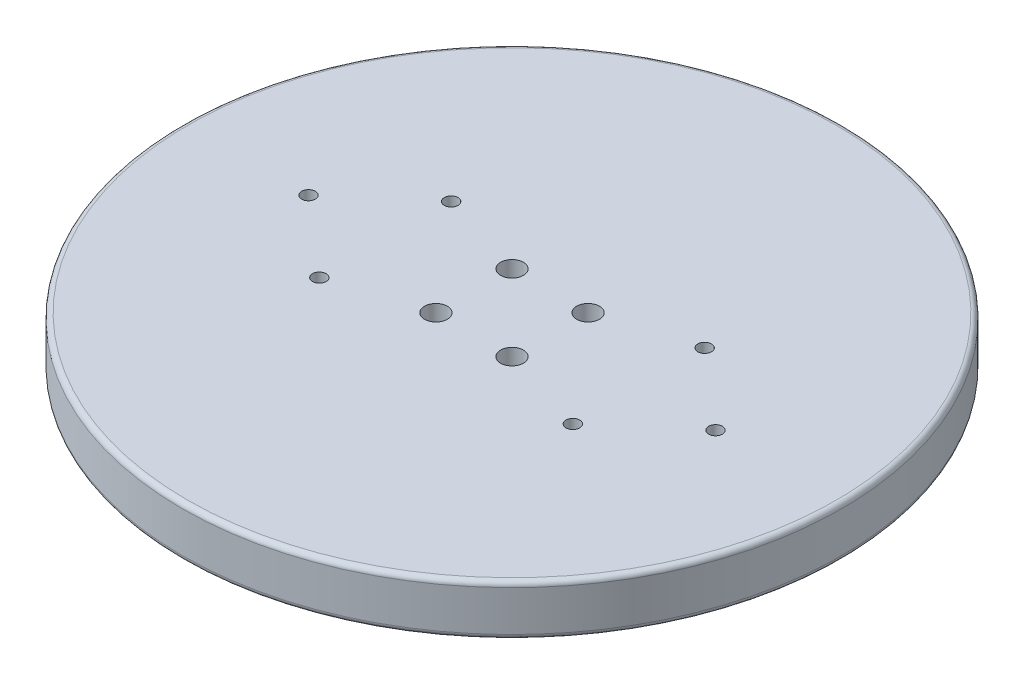
SolidWorks part; units mm, degrees
material "Delrin 2700 NC010, Low Viscosity Acetal Copolymer (SS)"
ref_plane "Front Plane" through (0, 0, 0) normal (0, 0, 1) x (1, 0, 0)
ref_plane "Top Plane" through (0, 0, 0) normal (0, 1, 0) x (1, 0, 0)
ref_plane "Right Plane" through (0, 0, 0) normal (1, 0, 0) x (0, 0, -1)
sketch "Sketch1" plane through (0, 0, 0) normal (0, 1, 0) x (1, 0, 0)
  circle A0 centre (0, 0) radius 65
  dimension "D1" = 130
extrude "Boss-Extrude1" add sketch "Sketch1" along normal blind 10
fillet "Fillet1" radius 1 2 edges at (0, 0, 65) (0, 10, 65)
hole_wizard "#6-32 Tapped Hole1" positions "Sketch2" profile "Sketch3" tap size "#6-32" standard "ANSI Inch" end condition through all
sketch "Sketch2" plane through (0, 0, 0) normal (0, 1, 0) x (1, 0, 0)
  point P0 (-40.14, 0)
  point P2 (40.14, 0)
  point P4 (-25, 13)
  point P6 (-25, -13)
  point P8 (25, -13)
  point P10 (25, 13)
  dimension "D1" = 40.14
  dimension "D2" = 40.14
  dimension "D3" = 25
  dimension "D4" = 25
  dimension "D5" = 13
  dimension "D6" = 13
sketch "Sketch3" plane through (-40.14, 0, 0) normal (1, 0, 0) x (0, 0, -1)
  line L0 (0, 0) -> (0, 10)
  line L1 (0, 10) -> (1.3525, 10)
  line L2 (1.3525, 10) -> (1.3525, 0)
  line L5 (1.3525, 0) -> (0, 0)
  line L11 (0, -6.35) -> (0, 107.95) construction
  dimension "Thru Tap Drill Dia." = 2.7051
  dimension "Thru Tap Drill Depth" = 10
cosmetic thread "Hole Thread1" parameters "D2"=3.5052
cosmetic thread "Hole Thread2" parameters "D2"=3.5052
cosmetic thread "Hole Thread3" parameters "D2"=3.5052
cosmetic thread "Hole Thread4" parameters "D2"=3.5052
cosmetic thread "Hole Thread5" parameters "D2"=3.5052
cosmetic thread "Hole Thread6" parameters "D2"=3.5052
hole_wizard "#4-40 Tapped Hole1" [suppressed] positions "Sketch5" profile "Sketch6" tap size "#4-40" standard "ANSI Inch"
sketch "Sketch5" plane through (0, 0, 0) normal (0, -1, 0) x (-1, 0, 0)
  circle A0 centre (-36.145, 0) radius 1.3526 construction
  point P0 (-48.145, 27.124)
  point P2 (-48.145, -27.124)
  dimension "D1" = 12
  dimension "D2" = 27.124
  dimension "D3" = 27.124
sketch "Sketch6" plane through (48.145, 0, -27.124) normal (1, 0, 0) x (0, 0, -1)
  line L0 (0, 0) -> (0, 25.4)
  line L1 (0, 25.4) -> (1.1303, 25.4)
  line L2 (1.1303, 25.4) -> (1.1303, 0)
  line L5 (1.1303, 0) -> (0, 0)
  line L11 (0, -6.35) -> (0, 107.95) construction
  dimension "Thru Tap Drill Dia." = 2.2606
  dimension "Thru Tap Drill Depth" = 25.4
cosmetic thread "Hole Thread7" [suppressed] parameters "D2"=2.8448
cosmetic thread "Hole Thread8" [suppressed] parameters "D2"=2.8448
hole_wizard "#8 Clearance Hole1" positions "Sketch7" profile "Sketch8" hole size "#8" standard "ANSI Inch" end condition through all
sketch "Sketch7" plane through (0, 0, 0) normal (0, -1, 0) x (-1, 0, 0)
  circle A0 centre (0, 0) radius 16.5 construction
  point P0 (7.5, -7.5)
  point P2 (-7.5, -7.5)
  point P4 (7.5, 7.5)
  point P6 (-7.5, 7.5)
  dimension "D5" = 33
  dimension "D1" = 7.5
  dimension "D2" = 7.5
  dimension "D3" = 7.5
  dimension "D4" = 7.5
sketch "Sketch8" plane through (-7.5, 0, 7.5) normal (1, 0, 0) x (0, 0, -1)
  line L0 (0, 0) -> (0, 10)
  line L1 (0, 10) -> (2.2479, 10)
  line L2 (2.2479, 10) -> (2.2479, 0)
  line L5 (2.2479, 0) -> (0, 0)
  line L11 (0, -6.35) -> (0, 107.95) construction
  dimension "Thru Hole Dia." = 4.4958
  dimension "Thru Hole Depth" = 10
equation "\"D2@Sketch2\"=\"D1@Sketch2\""
equation "\"D4@Sketch2\"=\"D3@Sketch2\""
equation "\"D6@Sketch2\"=\"D5@Sketch2\""
equation "\"D2@Sketch5\"=\"D3@Sketch5\""
equation "\"D2@Sketch7\"=\"D1@Sketch7\""
equation "\"D3@Sketch7\"=\"D4@Sketch7\""
equation "\"D1@Sketch2\"=25+15.14"
